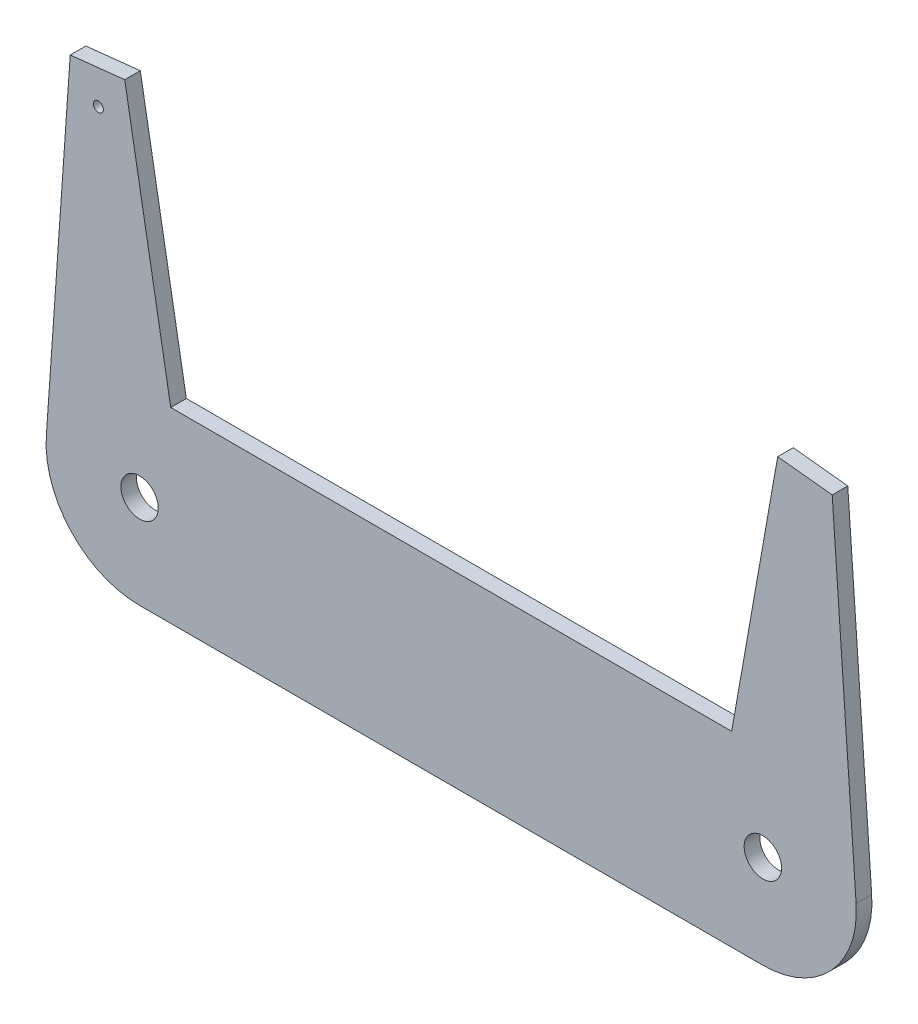
SolidWorks part; units mm, degrees
ref_plane "Front Plane" through (0, 0, 0) normal (0, 0, 1) x (1, 0, 0)
ref_plane "Top Plane" through (0, 0, 0) normal (0, 1, 0) x (1, 0, 0)
ref_plane "Right Plane" through (0, 0, 0) normal (1, 0, 0) x (0, 0, -1)
sketch "Sketch1" plane through (0, 0, 0) normal (0, 0, 1) x (1, 0, 0)
  line L1 (0, -30) -> (0, 90.9731) construction
  line L2 (100, 30) -> (-100, 30)
  line L3 (-100, -30) -> (100, -30)
  line L4 (90, 30) -> (-90, 30)
  line L5 (-100, -30) -> (100, -30)
  line L7 (-122.2537, 111.8247) -> (-104.7601, 113.7087)
  line L8 (-104.7601, 113.7087) -> (-90, 30)
  line L9 (-100, 30) -> (100, 30) construction
  line L14 (104.7601, 113.7087) -> (90, 30)
  line L15 (122.2537, 111.8247) -> (104.7601, 113.7087)
  line L16 (-122.2537, 111.8247) -> (-129.9269, 2.0927)
  line L21 (122.2537, 111.8247) -> (129.9269, 2.0927)
  circle A0 centre (-113.2117, 101.9985) radius 1.6
  circle A1 centre (-100, 0) radius 6
  arc A2 (100, -30) -> (100, 30) centre (100, 0) ccw
  arc A3 (-100, 30) -> (-100, -30) centre (-100, 0) ccw
  circle A6 centre (100, 0) radius 6
  arc A7 (100, -30) -> (129.9269, 2.0927) centre (100, 0) ccw
  arc A9 (-100, -30) -> (-129.9269, 2.0927) centre (-100, 0) cw
  point P6 (-109.77, 117.3547)
  point P8 (-122.4489, 118.1244)
  point P15 (-106.0558, 120.2228)
  point P18 (-122.4489, 119.0958)
  point P20 (-118.7849, 98.5355)
  point P26 (-109.0218, 121.5871)
  point P28 (-109.77, 117.3547)
  point P29 (-109.77, 117.3547)
  point P30 (-109.77, 117.3547)
  dimension "D9" = 3.2
  dimension "D10" = 12
  dimension "D2" = 110
  dimension "D3" = 86
  dimension "D5" = 80
  dimension "D7" = 85
  dimension "D8" = 90
  dimension "D1" = 0
extrude "Boss-Extrude1" add sketch "Sketch1" along normal blind 5
